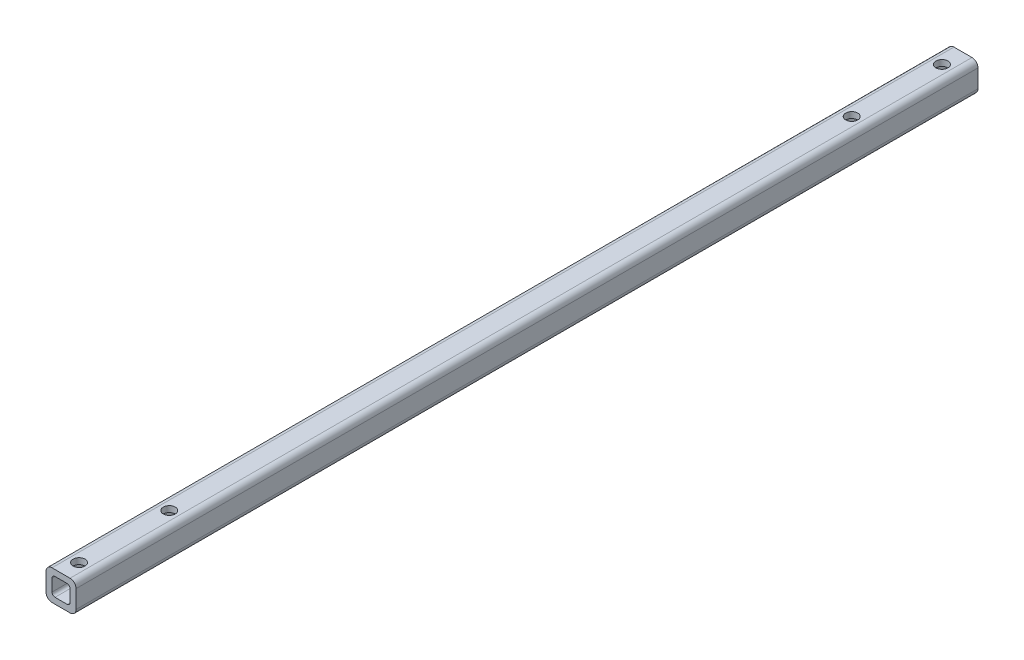
SolidWorks part; units mm, degrees
ref_plane "Plan de face" through (0, 0, 0) normal (0, 0, 1) x (1, 0, 0)
ref_plane "Plan de dessus" through (0, 0, 0) normal (0, 1, 0) x (1, 0, 0)
ref_plane "Plan de droite" through (0, 0, 0) normal (1, 0, 0) x (0, 0, -1)
sketch "Esquisse1" plane through (0, 0, 0) normal (0, 0, 1) x (1, 0, 0)
  line L1 (2, 0) -> (8, 0)
  line L2 (0, 2) -> (0, 8)
  line L3 (2, 10) -> (8, 10)
  line L4 (10, 2) -> (10, 8)
  line L5 (3, 8) -> (7, 8)
  line L6 (2, 7) -> (2, 3)
  line L7 (3, 2) -> (7, 2)
  line L8 (8, 7) -> (8, 3)
  arc A0 (7, 8) -> (8, 7) centre (7, 7) cw
  arc A1 (7, 2) -> (8, 3) centre (7, 3) ccw
  arc A2 (2, 3) -> (3, 2) centre (3, 3) ccw
  arc A3 (3, 8) -> (2, 7) centre (3, 7) ccw
  arc A4 (8, 10) -> (10, 8) centre (8, 8) cw
  arc A5 (8, 0) -> (10, 2) centre (8, 2) ccw
  arc A6 (2, 0) -> (0, 2) centre (2, 2) cw
  arc A7 (0, 8) -> (2, 10) centre (2, 8) cw
  point P11 (8, 8)
  point P18 (2, 8)
  point P21 (10, 10)
  point P26 (0, 0)
  point P29 (0, 10)
  dimension "D7" = 1
  dimension "D8" = 2
  dimension "D1" = 10
  dimension "D2" = 10
  dimension "D3" = 6
  dimension "D4" = 2
  dimension "D5" = 2
  dimension "D6" = 6
extrude "Boss.-Extru.1" add sketch "Esquisse1" along normal blind 300
sketch "Esquisse2" plane through (0, 10, 0) normal (0, 1, 0) x (1, 0, 0)
  line L0 (8, -300) -> (2, -300) construction
  line L1 (0, -300) -> (0, 0) construction
  line L2 (10, -300) -> (10, 0) construction
  line L3 (8, 0) -> (2, 0) construction
  circle A0 centre (5, -294) radius 2
  circle A1 centre (5, -264) radius 2
  circle A2 centre (5, -7) radius 2
  circle A3 centre (5, -37) radius 2
  dimension "D1" = 6
  dimension "D2" = 5
  dimension "D3" = 4
  dimension "D4" = 4
  dimension "D5" = 30
  dimension "D6" = 5
  dimension "D7" = 4
  dimension "D8" = 4
  dimension "D9" = 7
  dimension "D11" = 5
  dimension "D12" = 5
  dimension "D10" = 30
extrude "Enlèv. mat.-Extru.1" cut sketch "Esquisse2" against normal through all
